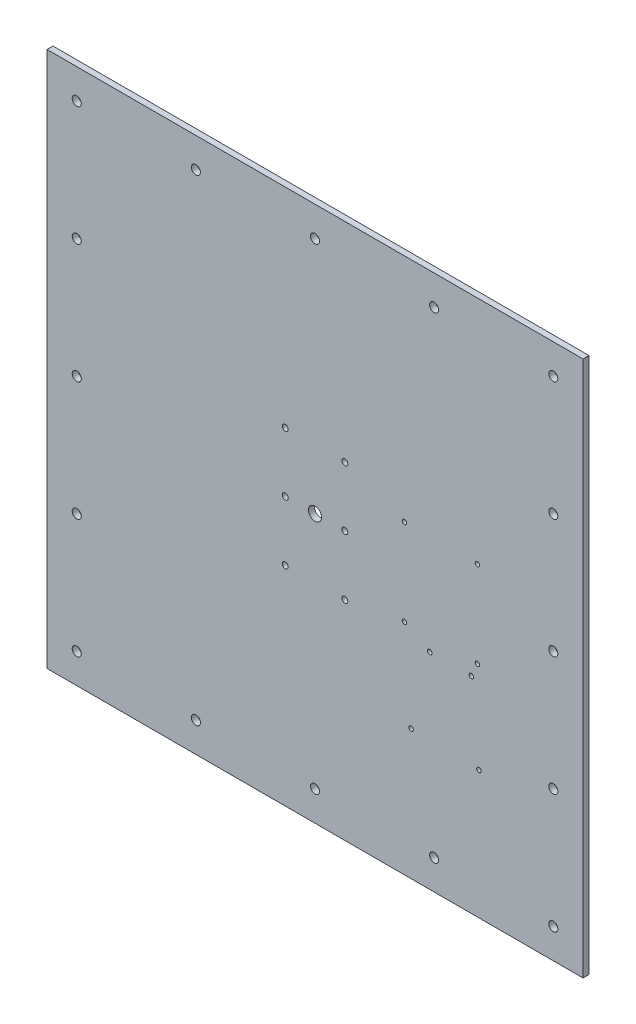
SolidWorks part; units mm, degrees
ref_plane "前视基准面" through (0, 0, 0) normal (0, 0, 1) x (1, 0, 0)
ref_plane "上视基准面" through (0, 0, 0) normal (0, 1, 0) x (1, 0, 0)
ref_plane "右视基准面" through (0, 0, 0) normal (1, 0, 0) x (0, 0, -1)
sketch "草图1" plane through (0, 0, 0) normal (0, 0, 1) x (1, 0, 0)
  line L0 (0, 19.5563) -> (0, -0.4437) construction
  line L1 (0, -0.4437) -> (-40, -0.4437) construction
  line L2 (0, 19.5563) -> (0, 85.5563) construction
  line L3 (-40, 39.5563) -> (-40, -0.4437) construction
  line L4 (-40, -0.4437) -> (-40, -40.4437) construction
  line L5 (-40, 39.5563) -> (0, 39.5563) construction
  line L6 (-20, -0.4437) -> (-20, 39.5563) construction
  line L7 (-100, 79.5563) -> (60, 79.5563) construction
  line L8 (-100, 79.5563) -> (-100, -80.4437) construction
  line L9 (-100, -80.4437) -> (60, -80.4437) construction
  line L10 (60, 79.5563) -> (60, -80.4437) construction
  line L11 (-100, 79.5563) -> (-100, 179.5563) construction
  line L12 (-200, 179.5563) -> (160, 179.5563)
  line L13 (-200, 179.5563) -> (-200, -180.4437)
  line L14 (-200, -180.4437) -> (160, -180.4437)
  line L15 (160, 179.5563) -> (160, -180.4437)
  line L16 (-100, -80.4437) -> (-200, -80.4437) construction
  line L17 (-100, -80.4437) -> (-100, -180.4437) construction
  line L18 (60, 79.5563) -> (160, 79.5563) construction
  circle A0 centre (0, 19.5563) radius 10 construction
  circle A2 centre (-40, -0.4437) radius 2
  circle A3 centre (-40, 39.5563) radius 2
  circle A4 centre (0, 39.5563) radius 2
  circle A5 centre (0, -0.4437) radius 2
  circle A6 centre (0, -40.4437) radius 2
  circle A7 centre (-40, -40.4437) radius 2
  circle A8 centre (-20, -0.4437) radius 4.4
  dimension "D2" = 4
  dimension "D11" = 100
  dimension "D3" = 40
  dimension "D4" = 40
  dimension "D5" = 40
  dimension "D6" = 40
  dimension "D7" = 60
  dimension "D8" = 80
  dimension "D9" = 80
  dimension "D10" = 80
extrude "凸台-拉伸1" add sketch "草图1" along normal blind 4
sketch "草图2" plane through (0, 0, 4) normal (0, 0, 1) x (1, 0, 0)
  line L0 (39.2612, -39.8138) -> (92.5612, -39.8138) construction
  line L1 (39.2612, -39.8138) -> (39.2612, -108.4138) construction
  line L2 (39.2612, -108.4138) -> (92.5612, -108.4138) construction
  line L3 (92.5612, -39.8138) -> (92.5612, -108.4138) construction
  line L4 (40.0612, 24.7685) -> (40.0612, -33.2315) construction
  line L5 (40.0612, 24.7685) -> (89.0612, 24.7685) construction
  line L6 (89.0612, 24.7685) -> (89.0612, -33.2315) construction
  line L7 (40.0612, -33.2315) -> (36.5612, -33.2315)
  line L8 (36.5612, 48.2685) -> (92.5612, 48.2685) construction
  line L9 (36.5612, 48.2685) -> (36.5612, -36.7315) construction
  line L10 (36.5612, -36.7315) -> (92.5612, -36.7315) construction
  line L11 (92.5612, 48.2685) -> (92.5612, -36.7315) construction
  line L12 (89.0612, -33.2315) -> (92.5612, -33.2315) construction
  circle A0 centre (57.0612, -42.3138) radius 1.5
  circle A1 centre (84.9612, -42.3138) radius 1.5
  circle A2 centre (44.5612, -93.1138) radius 1.5
  circle A3 centre (90.0612, -94.4138) radius 1.5
  circle A4 centre (40.0612, 24.7685) radius 1.5
  circle A5 centre (89.0612, 24.7685) radius 1.5
  circle A6 centre (40.0612, -33.2315) radius 1.5
  circle A7 centre (89.0612, -33.2315) radius 1.5
  point P26 (0, 0)
  point P27 (0, 0)
  point P28 (0, 0)
  dimension "D1" = 3
  dimension "D2" = 58
  dimension "D3" = 49
  dimension "D4" = 85
  dimension "D5" = 56
  dimension "D6" = 3.5
extrude "切除-拉伸2" cut sketch "草图2" against normal blind 20 contours A2 | A3 | A0 | A1 | A6 | A7 | A5 | A4
sketch "草图3" plane through (0, 0, 4) normal (0, 0, 1) x (1, 0, 0)
  line L0 (-200, 179.5563) -> (-200, -180.4437) construction
  line L1 (-180, 159.5563) -> (140, 159.5563) construction
  line L2 (-180, 159.5563) -> (-180, -160.4437) construction
  line L3 (-180, -160.4437) -> (140, -160.4437) construction
  line L4 (140, 159.5563) -> (140, -160.4437) construction
  line L5 (-180, 159.5563) -> (-200, 159.5563) construction
  line L6 (-180, 159.5563) -> (-180, 179.5563) construction
  line L7 (160, 179.5563) -> (-200, 179.5563) construction
  line L8 (-180, -160.4437) -> (-180, -180.4437) construction
  line L9 (-200, -180.4437) -> (160, -180.4437) construction
  line L10 (140, -160.4437) -> (160, -160.4437) construction
  line L11 (160, -180.4437) -> (160, 179.5563) construction
  circle A1 centre (-180, -160.4437) radius 3.04
  circle A2 centre (-180, -80.4437) radius 3.04
  circle A3 centre (-180, -0.4437) radius 3.04
  circle A4 centre (-180, 79.5563) radius 3.04
  circle A5 centre (-180, 159.5563) radius 3.04
  circle A6 centre (-100, 159.5563) radius 3.04
  circle A7 centre (-20, 159.5563) radius 3.04
  circle A8 centre (60, 159.5563) radius 3.04
  circle A9 centre (140, 159.5563) radius 3.04
  circle A10 centre (140, 79.5563) radius 3.04
  circle A11 centre (140, -0.4437) radius 3.04
  circle A12 centre (140, -80.4437) radius 3.04
  circle A13 centre (140, -160.4437) radius 3.04
  circle A14 centre (60, -160.4437) radius 3.04
  circle A15 centre (-20, -160.4437) radius 3.04
  circle A16 centre (-100, -160.4437) radius 3.04
  dimension "D2" = 6.08
  dimension "D1" = 20
  dimension "D3" = 4
  dimension "D4" = 4
extrude "切除-拉伸3" cut sketch "草图3" against normal blind 20
